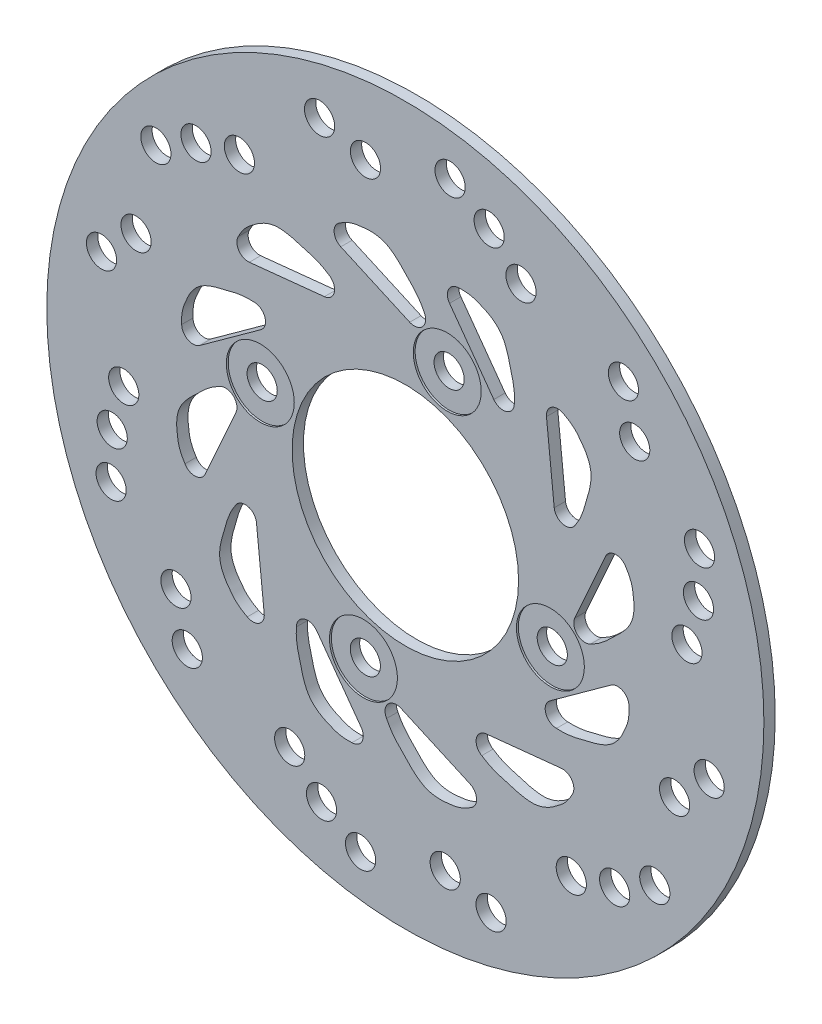
SolidWorks part; units mm, degrees
ref_plane "Front Plane" through (0, 0, 0) normal (0, 0, 1) x (1, 0, 0)
ref_plane "Top Plane" through (0, 0, 0) normal (0, 1, 0) x (1, 0, 0)
ref_plane "Right Plane" through (0, 0, 0) normal (1, 0, 0) x (0, 0, -1)
sketch "Sketch1" plane through (0, 0, 0) normal (0, 0, 1) x (1, 0, 0)
  circle A0 centre (0, 0) radius 95
  circle A1 centre (0, 0) radius 30
  dimension "D1" = 190
  dimension "D2" = 60
extrude "Boss-Extrude1" add sketch "Sketch1" along normal blind 3
sketch "Sketch2" plane through (0, 0, 3) normal (0, 0, 1) x (1, 0, 0)
  line L0 (0, 0) -> (-29.6939, 104.3397) construction
  line L1 (0, 0) -> (-14.3688, 103.7397) construction
  line L2 (0, 0) -> (14.3594, 100.7155) construction
  line L3 (0, 0) -> (29.3234, 101.4987) construction
  line L4 (0, 0) -> (43.6468, 97.5087) construction
  circle A0 centre (0, 0) radius 83 construction
  circle A1 centre (0, 0) radius 77 construction
  circle A2 centre (-22.7188, 79.8302) radius 4
  circle A3 centre (-10.5643, 76.2719) radius 4
  circle A4 centre (0, 0) radius 84 construction
  circle A5 centre (11.8563, 83.159) radius 4
  circle A6 centre (0, 0) radius 80 construction
  circle A7 centre (22.2042, 76.8568) radius 4
  circle A8 centre (0, 0) radius 75 construction
  circle A9 centre (30.6418, 68.455) radius 4
  dimension "D3" = 166
  dimension "D4" = 154
  dimension "D5" = 8
  dimension "D6" = 168
  dimension "D7" = 160
  dimension "D8" = 150
  dimension "D9" = 8
  dimension "D1" = 8
  dimension "D2" = 16
  dimension "D10" = 8
extrude "Cut-Extrude1" cut sketch "Sketch2" against normal up to next
pattern_circular "CirPattern1" count 6 over 360 about axis through (0, 0, 0) along (0, 0, 1) of "Cut-Extrude1"
sketch "Sketch3" plane through (0, 0, 3) normal (0, 0, 1) x (1, 0, 0)
  line L0 (0, 0) -> (29.2051, 101.0891) construction
  circle A0 centre (22.2042, 76.8568) radius 4 construction
  circle A1 centre (22.2042, 76.8568) radius 4
  circle A2 centre (0, 0) radius 40 construction
  circle A3 centre (11.1021, 38.4284) radius 9
  circle A4 centre (38.4284, -11.1021) radius 9
  circle A5 centre (-11.1021, -38.4284) radius 9
  circle A6 centre (-38.4284, 11.1021) radius 9
  point P18 (0, 0)
  dimension "D1" = 80
  dimension "D2" = 18
  dimension "D3" = 4
extrude "Cut-Extrude3" cut sketch "Sketch3" against normal blind 0.5
sketch "Sketch4" plane through (0, 0, 2.5) normal (0, 0, 1) x (1, 0, 0)
  circle A0 centre (11.1021, 38.4284) radius 4
  circle A2 centre (38.4284, -11.1021) radius 4
  circle A3 centre (-11.1021, -38.4284) radius 4
  circle A4 centre (-38.4284, 11.1021) radius 4
  point P12 (0, 0)
  dimension "D1" = 8
  dimension "D2" = 4
extrude "Cut-Extrude4" cut sketch "Sketch4" against normal through all
sketch "Sketch6" plane through (0, 0, 3) normal (0, 0, 1) x (1, 0, 0)
  line L0 (0, 0) -> (29.1334, 100.8411) construction
  line L1 (14.1436, 56.2491) -> (25.0866, 41.124) construction
  line L2 (0, 0) -> (25.4253, 101.1162) construction
  line L3 (11.7131, 54.4906) -> (23.4365, 38.2868)
  line L4 (16.4024, 48.0091) -> (25.3145, 54.4569) construction
  line L5 (37.3891, 41.3337) -> (39.44, 21.4391)
  line L6 (53.0467, 17.1015) -> (44.8756, -1.1532)
  line L7 (54.4906, -11.7131) -> (38.2868, -23.4365)
  line L8 (41.3337, -37.3891) -> (21.4391, -39.44)
  line L9 (17.1015, -53.0467) -> (-1.1532, -44.8756)
  line L10 (-11.7131, -54.4906) -> (-23.4365, -38.2868)
  line L11 (-37.3891, -41.3337) -> (-39.44, -21.4391)
  line L12 (-53.0467, -17.1015) -> (-44.8756, 1.1532)
  line L13 (-54.4906, 11.7131) -> (-38.2868, 23.4365)
  line L14 (-41.3337, 37.3891) -> (-21.4391, 39.44)
  line L15 (-17.1015, 53.0467) -> (1.1532, 44.8756)
  circle A0 centre (22.2042, 76.8568) radius 4 construction
  circle A1 centre (22.2042, 76.8568) radius 4
  circle A2 centre (0, 0) radius 58 construction
  arc A3 (14.1436, 59.2491) -> (11.7131, 54.4906) centre (14.1436, 56.2491) ccw
  arc A4 (23.4365, 38.2868) -> (28.8671, 40.0453) centre (25.8671, 40.0453) ccw
  arc A5 (41.8733, 44.2394) -> (37.3891, 41.3337) centre (40.3733, 41.6413) ccw
  arc A6 (39.44, 21.4391) -> (45.0223, 20.2467) centre (42.4242, 21.7467) ccw
  arc A7 (58.383, 17.3758) -> (53.0467, 17.1015) centre (55.7849, 15.8758) ccw
  arc A8 (44.8756, -1.1532) -> (49.1138, -4.9769) centre (47.6138, -2.3789) ccw
  arc A9 (59.2491, -14.1436) -> (54.4906, -11.7131) centre (56.2491, -14.1436) ccw
  arc A10 (38.2868, -23.4365) -> (40.0453, -28.8671) centre (40.0453, -25.8671) ccw
  arc A11 (44.2394, -41.8733) -> (41.3337, -37.3891) centre (41.6413, -40.3733) ccw
  arc A12 (21.4391, -39.44) -> (20.2467, -45.0223) centre (21.7467, -42.4242) ccw
  arc A13 (17.3758, -58.383) -> (17.1015, -53.0467) centre (15.8758, -55.7849) ccw
  arc A14 (-1.1532, -44.8756) -> (-4.9769, -49.1138) centre (-2.3789, -47.6138) ccw
  arc A15 (-14.1436, -59.2491) -> (-11.7131, -54.4906) centre (-14.1436, -56.2491) ccw
  arc A16 (-23.4365, -38.2868) -> (-28.8671, -40.0453) centre (-25.8671, -40.0453) ccw
  arc A17 (-41.8733, -44.2394) -> (-37.3891, -41.3337) centre (-40.3733, -41.6413) ccw
  arc A18 (-39.44, -21.4391) -> (-45.0223, -20.2467) centre (-42.4242, -21.7467) ccw
  arc A19 (-58.383, -17.3758) -> (-53.0467, -17.1015) centre (-55.7849, -15.8758) ccw
  arc A20 (-44.8756, 1.1532) -> (-49.1138, 4.9769) centre (-47.6138, 2.3789) ccw
  arc A21 (-59.2491, 14.1436) -> (-54.4906, 11.7131) centre (-56.2491, 14.1436) ccw
  arc A22 (-38.2868, 23.4365) -> (-40.0453, 28.8671) centre (-40.0453, 25.8671) ccw
  arc A23 (-44.2394, 41.8733) -> (-41.3337, 37.3891) centre (-41.6413, 40.3733) ccw
  arc A24 (-21.4391, 39.44) -> (-20.2467, 45.0223) centre (-21.7467, 42.4242) ccw
  arc A25 (-17.3758, 58.383) -> (-17.1015, 53.0467) centre (-15.8758, 55.7849) ccw
  arc A26 (1.1532, 44.8756) -> (4.9769, 49.1138) centre (2.3789, 47.6138) ccw
  spline S0 degree 3 poles (14.1436, 59.2491) (17.597, 59.43) (19.2244, 58.427) (21.5251, 57.5786) (26.0208, 55.1392) (27.4548, 49.5445) (29.1152, 42.508) (28.8611, 40.9573) (28.8671, 40.0453) knots 0 0 0 0 0.283285 0.338844 0.555593 0.777993 0.822434 1 1 1 1
  spline S1 degree 3 poles (41.8733, 44.2394) (44.9545, 42.6694) (45.8623, 40.9871) (47.4306, 39.102) (50.1043, 34.7416) (48.5488, 29.1794) (46.4685, 22.2554) (45.4731, 21.0395) (45.0223, 20.2467) knots 0 0 0 0 0.283285 0.338844 0.555593 0.777993 0.822434 1 1 1 1
  spline S2 degree 3 poles (58.383, 17.3758) (60.2664, 14.4755) (60.2115, 12.5647) (60.6271, 10.148) (60.7624, 5.0349) (56.6342, 0.9957) (51.3706, -3.9605) (49.9006, -4.5158) (49.1138, -4.9769) knots 0 0 0 0 0.283285 0.338844 0.555593 0.777993 0.822434 1 1 1 1
  spline S3 degree 3 poles (59.2491, -14.1436) (59.43, -17.597) (58.427, -19.2244) (57.5786, -21.5251) (55.1392, -26.0208) (49.5445, -27.4548) (42.508, -29.1152) (40.9573, -28.8611) (40.0453, -28.8671) knots 0 0 0 0 0.283285 0.338844 0.555593 0.777993 0.822434 1 1 1 1
  spline S4 degree 3 poles (44.2394, -41.8733) (42.6694, -44.9545) (40.9871, -45.8623) (39.102, -47.4306) (34.7416, -50.1043) (29.1794, -48.5488) (22.2554, -46.4685) (21.0395, -45.4731) (20.2467, -45.0223) knots 0 0 0 0 0.283285 0.338844 0.555593 0.777993 0.822434 1 1 1 1
  spline S5 degree 3 poles (17.3758, -58.383) (14.4755, -60.2664) (12.5647, -60.2115) (10.148, -60.6271) (5.0349, -60.7624) (0.9957, -56.6342) (-3.9605, -51.3706) (-4.5158, -49.9006) (-4.9769, -49.1138) knots 0 0 0 0 0.283285 0.338844 0.555593 0.777993 0.822434 1 1 1 1
  spline S6 degree 3 poles (-14.1436, -59.2491) (-17.597, -59.43) (-19.2244, -58.427) (-21.5251, -57.5786) (-26.0208, -55.1392) (-27.4548, -49.5445) (-29.1152, -42.508) (-28.8611, -40.9573) (-28.8671, -40.0453) knots 0 0 0 0 0.283285 0.338844 0.555593 0.777993 0.822434 1 1 1 1
  spline S7 degree 3 poles (-41.8733, -44.2394) (-44.9545, -42.6694) (-45.8623, -40.9871) (-47.4306, -39.102) (-50.1043, -34.7416) (-48.5488, -29.1794) (-46.4685, -22.2554) (-45.4731, -21.0395) (-45.0223, -20.2467) knots 0 0 0 0 0.283285 0.338844 0.555593 0.777993 0.822434 1 1 1 1
  spline S8 degree 3 poles (-58.383, -17.3758) (-60.2664, -14.4755) (-60.2115, -12.5647) (-60.6271, -10.148) (-60.7624, -5.0349) (-56.6342, -0.9957) (-51.3706, 3.9605) (-49.9006, 4.5158) (-49.1138, 4.9769) knots 0 0 0 0 0.283285 0.338844 0.555593 0.777993 0.822434 1 1 1 1
  spline S9 degree 3 poles (-59.2491, 14.1436) (-59.43, 17.597) (-58.427, 19.2244) (-57.5786, 21.5251) (-55.1392, 26.0208) (-49.5445, 27.4548) (-42.508, 29.1152) (-40.9573, 28.8611) (-40.0453, 28.8671) knots 0 0 0 0 0.283285 0.338844 0.555593 0.777993 0.822434 1 1 1 1
  spline S10 degree 3 poles (-44.2394, 41.8733) (-42.6694, 44.9545) (-40.9871, 45.8623) (-39.102, 47.4306) (-34.7416, 50.1043) (-29.1794, 48.5488) (-22.2554, 46.4685) (-21.0395, 45.4731) (-20.2467, 45.0223) knots 0 0 0 0 0.283285 0.338844 0.555593 0.777993 0.822434 1 1 1 1
  spline S11 degree 3 poles (-17.3758, 58.383) (-14.4755, 60.2664) (-12.5647, 60.2115) (-10.148, 60.6271) (-5.0349, 60.7624) (-0.9957, 56.6342) (3.9605, 51.3706) (4.5158, 49.9006) (4.9769, 49.1138) knots 0 0 0 0 0.283285 0.338844 0.555593 0.777993 0.822434 1 1 1 1
  point P121 (0, 0)
  dimension "D1" = 116
  dimension "D2" = 6
  dimension "D4" = 6
  dimension "D3" = 50
  dimension "D5" = 2
  dimension "D6" = 8
  dimension "D7" = 11
  dimension "D8" = 20
  dimension "D9" = 12
extrude "Cut-Extrude6" cut sketch "Sketch6" against normal through all
